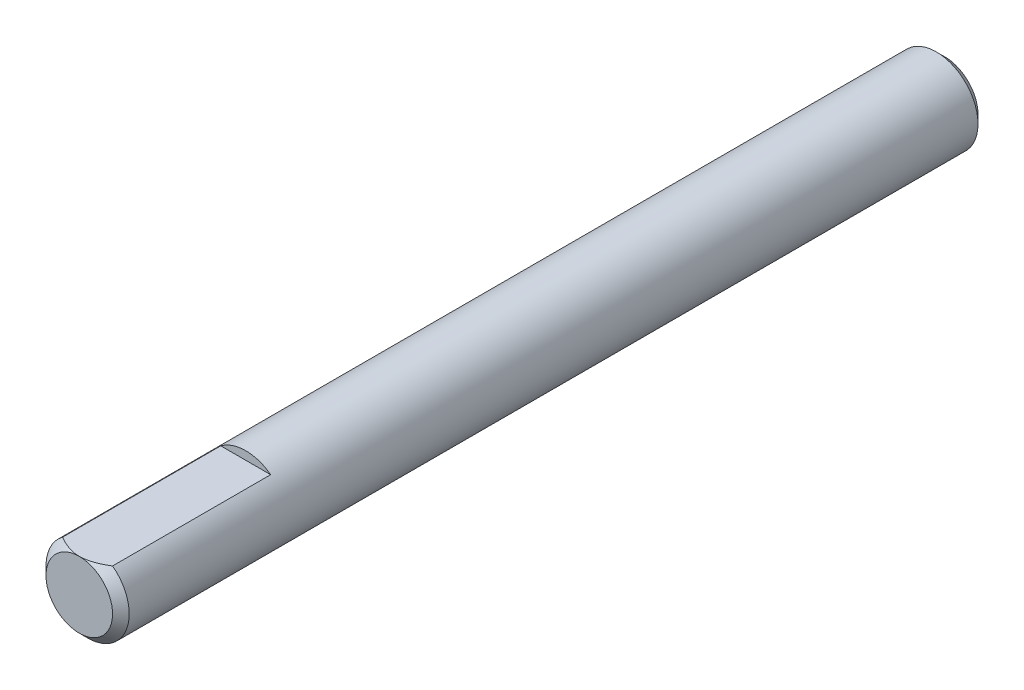
SolidWorks part; units mm, degrees
ref_plane "Front Plane" through (0, 0, 0) normal (0, 0, 1) x (1, 0, 0)
ref_plane "Top Plane" through (0, 0, 0) normal (0, 1, 0) x (1, 0, 0)
ref_plane "Right Plane" through (0, 0, 0) normal (1, 0, 0) x (0, 0, -1)
sketch "Sketch1" plane through (0, 0, 0) normal (0, 0, 1) x (1, 0, 0)
  circle A0 centre (0, 0) radius 2.5
  dimension "D1" = 5
extrude "Boss-Extrude1" add sketch "Sketch1" against normal blind 52
chamfer "Chamfer1" distance 0.5 angle 45 2 edges at (2.5, 0, -52) (2.5, 0, 0)
sketch "Sketch2" plane through (0, 0, 0) normal (0, 0, 1) x (1, 0, 0)
  line L0 (-1.5, 2) -> (1.5, 2)
  circle A0 centre (0, 0) radius 2.5 construction
  arc A1 (1.5, 2) -> (-1.5, 2) centre (0, 0) ccw
  dimension "D1" = 2
extrude "Cut-Extrude1" cut sketch "Sketch2" against normal blind 10
